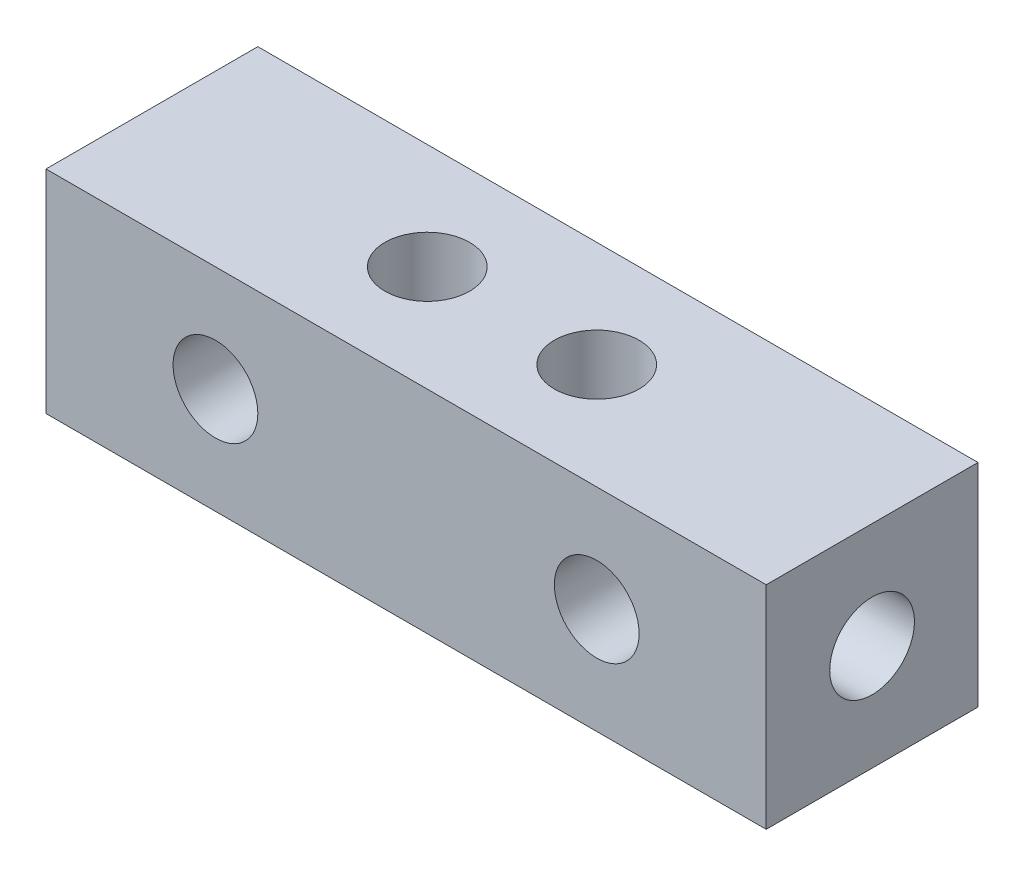
SolidWorks part; units mm, degrees
ref_plane "前视基准面" through (0, 0, 0) normal (0, 0, 1) x (1, 0, 0)
ref_plane "上视基准面" through (0, 0, 0) normal (0, 1, 0) x (1, 0, 0)
ref_plane "右视基准面" through (0, 0, 0) normal (1, 0, 0) x (0, 0, -1)
other "Configuration Table"
sketch "草图1" plane through (0, 0, 0) normal (0, 1, 0) x (1, 0, 0)
  line L1 (-17, 5) -> (17, 5)
  line L2 (-17, 5) -> (-17, -5)
  line L3 (-17, -5) -> (17, -5)
  line L4 (17, 5) -> (17, -5)
  line L5 (-17, 5) -> (17, -5) construction
  line L6 (-17, -5) -> (17, 5) construction
  point P0 (0, 0)
  dimension "D1" = 10
  dimension "D2" = 34
extrude "凸台-拉伸1" add sketch "草图1" along normal blind 10
sketch "草图2" plane through (0, 0, 5) normal (0, 0, 1) x (1, 0, 0)
  line L0 (-9, 5) -> (9, 5) construction
  line L1 (0, 5) -> (0, 0) construction
  circle A0 centre (-9, 5) radius 2
  circle A1 centre (9, 5) radius 2
  dimension "D2" = 4
  dimension "D1" = 5
  dimension "D3" = 18
extrude "切除-拉伸1" cut sketch "草图2" against normal blind 10
sketch "草图3" plane through (0, 10, 0) normal (0, 1, 0) x (1, 0, 0)
  line L0 (-4, 0) -> (4, 0) construction
  circle A0 centre (-4, 0) radius 2
  circle A1 centre (4, 0) radius 2
  point P4 (0, 0)
  dimension "D2" = 4
  dimension "D1" = 8
extrude "切除-拉伸2" cut sketch "草图3" against normal blind 10
sketch "草图4" plane through (-17, 0, 0) normal (-1, 0, 0) x (0, 0, 1)
  line L0 (0, 5) -> (5, 5) construction
  line L1 (5, 10) -> (5, 0) construction
  line L2 (0, 5) -> (0, 0) construction
  line L3 (-5, 0) -> (5, 0) construction
  circle A0 centre (0, 5) radius 2
  dimension "D1" = 4
extrude "切除-拉伸3" cut sketch "草图4" against normal blind 8
mirror "镜向1" about plane through (0, 0, 0) normal (1, 0, 0) of "切除-拉伸3"
